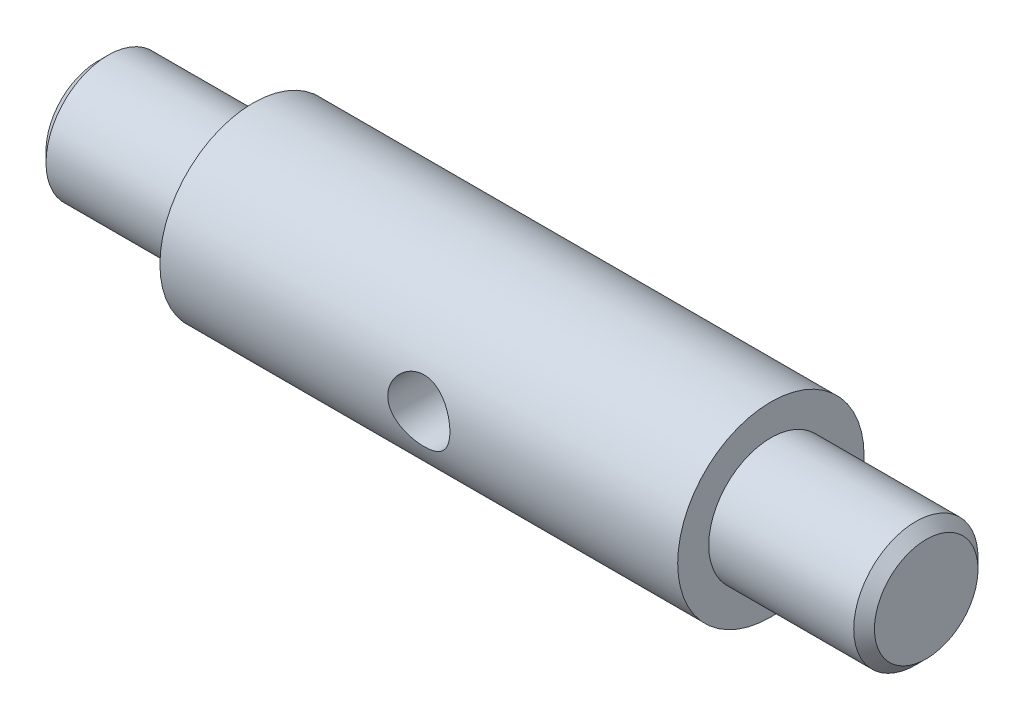
SolidWorks part; units mm, degrees
ref_plane "Front Plane" through (0, 0, 0) normal (0, 0, 1) x (1, 0, 0)
ref_plane "Top Plane" through (0, 0, 0) normal (0, 1, 0) x (1, 0, 0)
ref_plane "Right Plane" through (0, 0, 0) normal (1, 0, 0) x (0, 0, -1)
sketch "Sketch1" plane through (0, 0, 0) normal (0, 0, 1) x (1, 0, 0)
  line L0 (0, 0) -> (80, 0)
  line L1 (80, 0) -> (80, 6)
  line L2 (80, 6) -> (65, 6)
  line L3 (65, 6) -> (65, 9)
  line L4 (65, 9) -> (15, 9)
  line L5 (15, 9) -> (15, 6)
  line L6 (15, 6) -> (0, 6)
  line L7 (0, 6) -> (0, 0)
  dimension "D1" = 15
  dimension "D2" = 50
  dimension "D3" = 6
  dimension "D4" = 9
revolve "Revolve1" add sketch "Sketch1" angle 360 about L0
sketch "Sketch2" plane through (0, 0, 0) normal (0, 0, 1) x (1, 0, 0)
  line L0 (15, 9) -> (15, -9) construction
  circle A0 centre (40, 0) radius 3
  dimension "D2" = 6
  dimension "D1" = 25
extrude "Cut-Extrude1" cut sketch "Sketch2" against normal through all both and the other way through all
chamfer "Chamfer1" distance 1 angle 45 2 edges at (80, 0, 6) (0, 0, 6)
hole_wizard "Ø6.0 (6) Diameter Hole1" positions "Sketch3" profile "Sketch4" hole size "Ø6.0" standard "DIN"
sketch "Sketch3" plane through (0, 0, 0) normal (-1, 0, 0) x (0, 0, 1)
  point P0 (0, 0)
sketch "Sketch4" plane through (0, 0, 0) normal (0, 1, 0) x (0, 0, 1)
  line L0 (0, 0) -> (0, 46.8026)
  line L1 (0, 46.8026) -> (3, 45)
  line L2 (3, 45) -> (3, 0)
  line L5 (3, 0) -> (0, 0)
  line L10 (0, 46.8026) -> (-3, 45) construction
  line L11 (0, -6.35) -> (0, 107.95) construction
  dimension "Hole Dia." = 6
  dimension "Hole Depth" = 45
  dimension "Drill Angle" = 118
